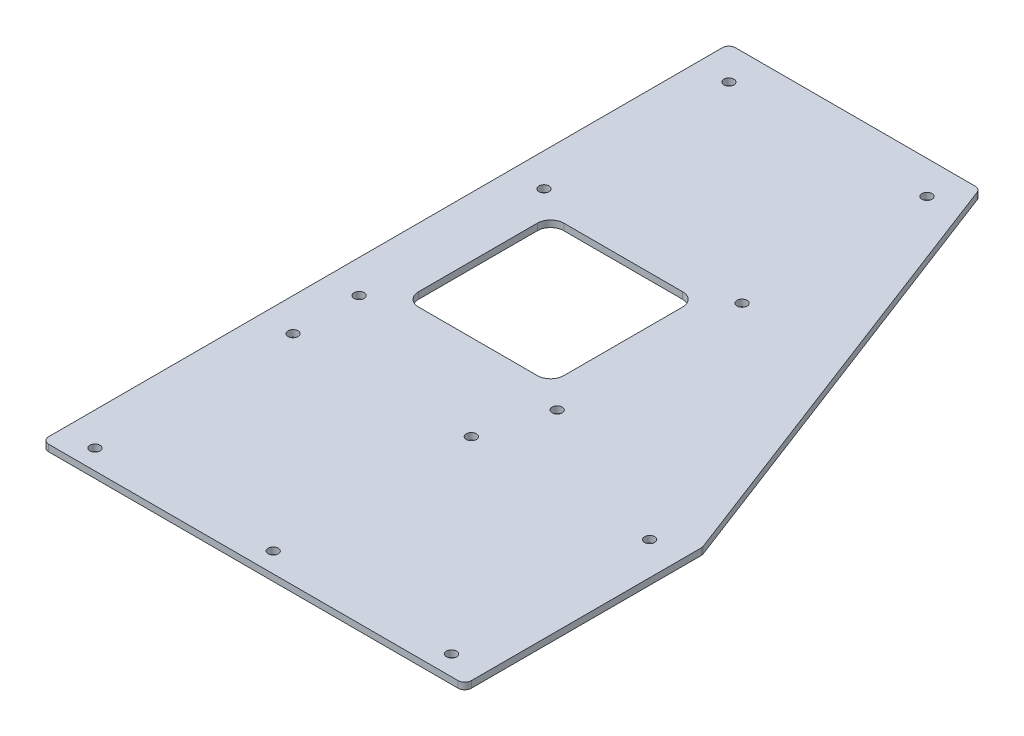
SolidWorks part; units mm, degrees
material "5052-H32"
ref_plane "Front" through (0, 0, 0) normal (0, 0, 1) x (1, 0, 0)
ref_plane "Top" through (0, 0, 0) normal (0, 1, 0) x (1, 0, 0)
ref_plane "Right" through (0, 0, 0) normal (1, 0, 0) x (0, 0, -1)
sketch "Sketch1" plane through (0, 0, 0) normal (0, 1, 0) x (1, 0, 0)
  line L0 (0, 0) -> (203.2, 0)
  line L1 (203.2, 0) -> (203.2, 114.3)
  line L2 (0, 0) -> (0, 330.2)
  line L3 (0, 330.2) -> (120.65, 330.2)
  line L4 (120.65, 330.2) -> (203.2, 114.3)
  line L5 (203.2, 114.3) -> (0, 114.3) construction
  line L6 (120.65, 330.2) -> (120.65, 114.3) construction
  line L7 (15.875, 136.525) -> (15.875, 314.325) construction
  line L8 (111.125, 136.525) -> (111.125, 314.325) construction
  line L9 (15.875, 314.325) -> (111.125, 314.325) construction
  circle A0 centre (15.875, 9.525) radius 2.4257
  circle A1 centre (101.6, 9.525) radius 2.4257
  circle A2 centre (187.325, 9.525) radius 2.4257
  circle A3 centre (15.875, 104.775) radius 2.4257
  circle A5 centre (187.325, 104.775) radius 2.4257
  circle A7 centre (101.6, 104.775) radius 2.4257
  circle A8 centre (15.875, 136.525) radius 2.4257
  circle A9 centre (111.125, 136.525) radius 2.4257
  circle A10 centre (15.875, 225.425) radius 2.4257
  circle A11 centre (15.875, 314.325) radius 2.4257
  circle A12 centre (111.125, 225.425) radius 2.4257
  circle A13 centre (111.125, 314.325) radius 2.4257
  dimension "D5" = 4.8514
  dimension "D1" = 203.2
  dimension "D2" = 114.3
  dimension "D3" = 9.525
  dimension "D4" = 15.875
  dimension "D7" = 85.725
  dimension "D9" = 95.25
  dimension "D10" = 330.2
  dimension "D11" = 22.225
  dimension "D12" = 95.25
  dimension "D13" = 15.875
  dimension "D14" = 120.65
  dimension "D6" = 3
  dimension "D8" = 2
extrude "Boss-Extrude1" add sketch "Sketch1" along normal blind 3.175
fillet "Fillet1" radius 3.175 5 edges at (0, 1.5875, -330.2) (120.65, 1.5875, -330.2) (203.2, 1.5875, -114.3) (0, 1.5875, 0) (203.2, 1.5875, 0)
sketch "Sketch2" plane through (0, 3.175, 0) normal (0, 1, 0) x (1, 0, 0)
  line L0 (15.875, 225.425) -> (111.125, 225.425) construction
  line L1 (15.875, 136.525) -> (111.125, 136.525) construction
  line L6 (63.5, 136.525) -> (63.5, 225.425) construction
  line L8 (28.575, 215.9) -> (98.425, 215.9)
  line L9 (28.575, 215.9) -> (28.575, 146.05)
  line L10 (28.575, 146.05) -> (98.425, 146.05)
  line L11 (98.425, 215.9) -> (98.425, 146.05)
  line L12 (28.575, 215.9) -> (98.425, 146.05) construction
  line L13 (28.575, 146.05) -> (98.425, 215.9) construction
  point P9 (63.5, 180.975)
  dimension "D1" = 69.85
extrude "Cut-Extrude1" cut sketch "Sketch2" against normal through all
fillet "Fillet3" radius 6.35 4 edges at (98.425, 1.5875, -146.05) (28.575, 1.5875, -146.05) (98.425, 1.5875, -215.9) (28.575, 1.5875, -215.9)
